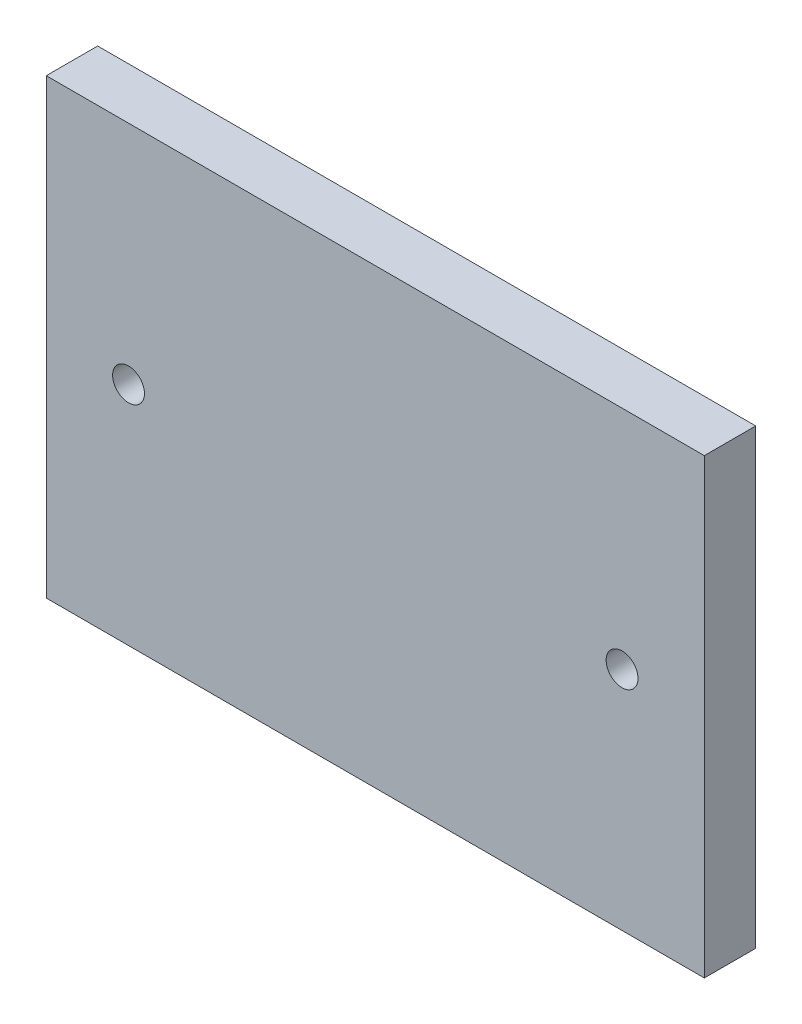
SolidWorks part; units mm, degrees
ref_plane "前视基准面" through (0, 0, 0) normal (0, 0, 1) x (1, 0, 0)
ref_plane "上视基准面" through (0, 0, 0) normal (0, 1, 0) x (1, 0, 0)
ref_plane "右视基准面" through (0, 0, 0) normal (1, 0, 0) x (0, 0, -1)
sketch "草图1" plane through (0, 0, 0) normal (0, 0, 1) x (1, 0, 0)
  line L1 (-32, -22) -> (32, -22)
  line L2 (-32, -22) -> (-32, 22)
  line L3 (-32, 22) -> (32, 22)
  line L4 (32, -22) -> (32, 22)
  line L5 (-32, -22) -> (32, 22) construction
  line L6 (-32, 22) -> (32, -22) construction
  dimension "D1" = 32
  dimension "D2" = 32
  dimension "D3" = 22
  dimension "D4" = 22
extrude "模拟5mm车架_非整车底板模型" add sketch "草图1" along normal blind 5 from offset 27
sketch "草图2" plane through (0, 0, 0) normal (0, 0, 1) x (1, 0, 0)
  circle A0 centre (-24, 0) radius 1.55
  circle A1 centre (24, 0) radius 1.55
  dimension "D1" = 3.1
  dimension "D2" = 24
  dimension "D3" = 24
extrude "检具48孔距" cut sketch "草图2" along normal blind 5 from offset 27
